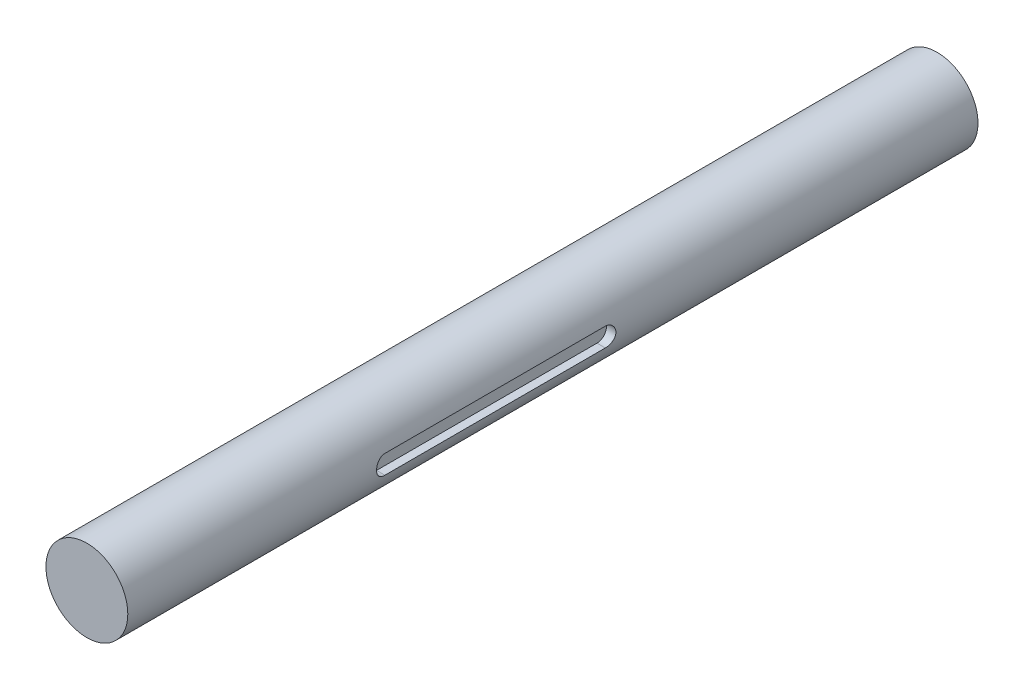
SolidWorks part; units mm, degrees
material "201 Annealed Stainless Steel (SS)"
ref_plane "Front Plane" through (0, 0, 0) normal (0, 0, 1) x (1, 0, 0)
ref_plane "Top Plane" through (0, 0, 0) normal (0, 1, 0) x (1, 0, 0)
ref_plane "Right Plane" through (0, 0, 0) normal (1, 0, 0) x (0, 0, -1)
sketch "Sketch1" plane through (0, 0, 0) normal (0, 0, 1) x (1, 0, 0)
  circle A0 centre (0, 0) radius 6.5
  dimension "D1" = 13
extrude "Boss-Extrude1" add sketch "Sketch1" along normal mid plane 135 contours A0
sketch "Sketch2" plane through (0, 0, 0) normal (1, 0, 0) x (0, 0, -1)
  line L0 (-26.5, 0) -> (8.5, 0) construction
  line L1 (-26.5, 1.5) -> (8.5, 1.5)
  line L2 (-26.5, -1.5) -> (8.5, -1.5)
  line L3 (0, 0) -> (-50000, 0) construction
  line L4 (-67.5, 6.5) -> (-67.5, -6.5) construction
  arc A0 (-26.5, 1.5) -> (-26.5, -1.5) centre (-26.5, 0) ccw
  arc A1 (8.5, -1.5) -> (8.5, 1.5) centre (8.5, 0) ccw
  point P2 (-9, 0)
  point P7 (10, 0)
  point P8 (-28, 0)
  point P12 (-9.758, 0)
  point P15 (0, 0)
  dimension "D1" = 38
  dimension "D2" = 3
  dimension "D3" = 39.5
extrude "Cut-Extrude1" cut sketch "Sketch2" against normal blind 1.5 from offset 6.5
